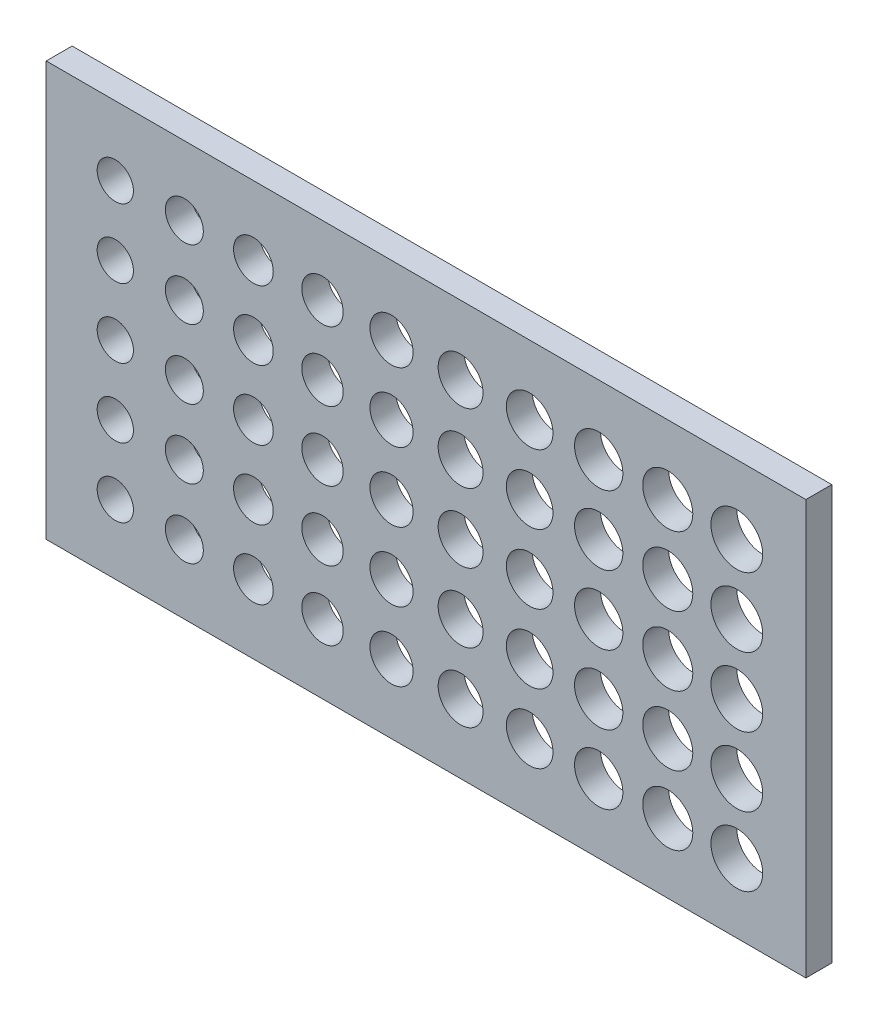
SolidWorks part; units mm, degrees
ref_plane "Front Plane" through (0, 0, 0) normal (0, 0, 1) x (1, 0, 0)
ref_plane "Top Plane" through (0, 0, 0) normal (0, 1, 0) x (1, 0, 0)
ref_plane "Right Plane" through (0, 0, 0) normal (1, 0, 0) x (0, 0, -1)
sketch "草图3" plane through (0, 0, 0) normal (0, 0, 1) x (1, 0, 0)
  line L1 (0, 0) -> (44, 0)
  line L2 (0, 0) -> (0, 24)
  line L3 (0, 24) -> (44, 24)
  line L4 (44, 0) -> (44, 24)
  point P5 (0, 0)
extrude "凸台-拉伸2" add sketch "草图3" along normal blind 1.5
sketch "草图4" plane through (0, 0, 0) normal (0, 0, 1) x (1, 0, 0)
  circle A0 centre (4, 4) radius 1.05
  circle A1 centre (4, 8) radius 1.05
  circle A2 centre (4, 12) radius 1.05
  circle A3 centre (4, 16) radius 1.05
  circle A4 centre (4, 20) radius 1.05
  dimension "D1" = 5
extrude "切除-拉伸1" cut sketch "草图4" along normal blind 1.5
sketch "草图5" plane through (0, 0, 0) normal (0, 0, 1) x (1, 0, 0)
  circle A0 centre (8, 4) radius 1.1
  circle A1 centre (8, 8) radius 1.1
  circle A2 centre (8, 12) radius 1.1
  circle A3 centre (8, 16) radius 1.1
  circle A4 centre (8, 20) radius 1.1
  dimension "D1" = 5
extrude "切除-拉伸2" cut sketch "草图5" along normal blind 1.5
sketch "草图6" plane through (0, 0, 0) normal (0, 0, 1) x (1, 0, 0)
  circle A0 centre (12, 4) radius 1.15
  circle A1 centre (12, 8) radius 1.15
  circle A2 centre (12, 12) radius 1.15
  circle A3 centre (12, 16) radius 1.15
  circle A4 centre (12, 20) radius 1.15
  dimension "D1" = 5
extrude "切除-拉伸3" cut sketch "草图6" along normal blind 1.5
sketch "草图7" plane through (0, 0, 0) normal (0, 0, 1) x (1, 0, 0)
  circle A0 centre (16, 4) radius 1.2
  circle A1 centre (16, 8) radius 1.2
  circle A2 centre (16, 12) radius 1.2
  circle A3 centre (16, 16) radius 1.2
  circle A4 centre (16, 20) radius 1.2
  dimension "D1" = 5
extrude "切除-拉伸4" cut sketch "草图7" along normal blind 1.5
sketch "草图8" plane through (0, 0, 0) normal (0, 0, 1) x (1, 0, 0)
  circle A0 centre (20, 4) radius 1.25
  circle A1 centre (20, 8) radius 1.25
  circle A2 centre (20, 12) radius 1.25
  circle A3 centre (20, 16) radius 1.25
  circle A4 centre (20, 20) radius 1.25
  dimension "D1" = 5
extrude "切除-拉伸6" cut sketch "草图8" along normal blind 1.5
sketch "草图10" plane through (0, 0, 0) normal (0, 0, 1) x (1, 0, 0)
  circle A0 centre (24, 4) radius 1.3
  circle A1 centre (24, 8) radius 1.3
  circle A2 centre (24, 12) radius 1.3
  circle A3 centre (24, 16) radius 1.3
  circle A4 centre (24, 20) radius 1.3
  dimension "D1" = 5
extrude "切除-拉伸7" cut sketch "草图10" along normal blind 1.5
sketch "草图11" plane through (0, 0, 0) normal (0, 0, 1) x (1, 0, 0)
  circle A0 centre (28, 4) radius 1.35
  circle A1 centre (28, 8) radius 1.35
  circle A2 centre (28, 12) radius 1.35
  circle A3 centre (28, 16) radius 1.35
  circle A4 centre (28, 20) radius 1.35
  dimension "D1" = 5
extrude "切除-拉伸8" cut sketch "草图11" along normal blind 1.5
sketch "草图12" plane through (0, 0, 0) normal (0, 0, 1) x (1, 0, 0)
  circle A0 centre (32, 4) radius 1.4
  circle A1 centre (32, 8) radius 1.4
  circle A2 centre (32, 12) radius 1.4
  circle A3 centre (32, 16) radius 1.4
  circle A4 centre (32, 20) radius 1.4
  dimension "D1" = 5
extrude "切除-拉伸9" cut sketch "草图12" along normal blind 1.5
sketch "草图13" plane through (0, 0, 0) normal (0, 0, 1) x (1, 0, 0)
  circle A0 centre (36, 4) radius 1.45
  circle A1 centre (36, 8) radius 1.45
  circle A2 centre (36, 12) radius 1.45
  circle A3 centre (36, 16) radius 1.45
  circle A4 centre (36, 20) radius 1.45
  dimension "D1" = 5
extrude "切除-拉伸10" cut sketch "草图13" along normal blind 1.5
sketch "草图14" plane through (0, 0, 0) normal (0, 0, 1) x (1, 0, 0)
  circle A0 centre (40, 4) radius 1.5
  circle A1 centre (40, 8) radius 1.5
  circle A2 centre (40, 12) radius 1.5
  circle A3 centre (40, 16) radius 1.5
  circle A4 centre (40, 20) radius 1.5
  dimension "D1" = 5
extrude "切除-拉伸11" cut sketch "草图14" along normal blind 1.5
